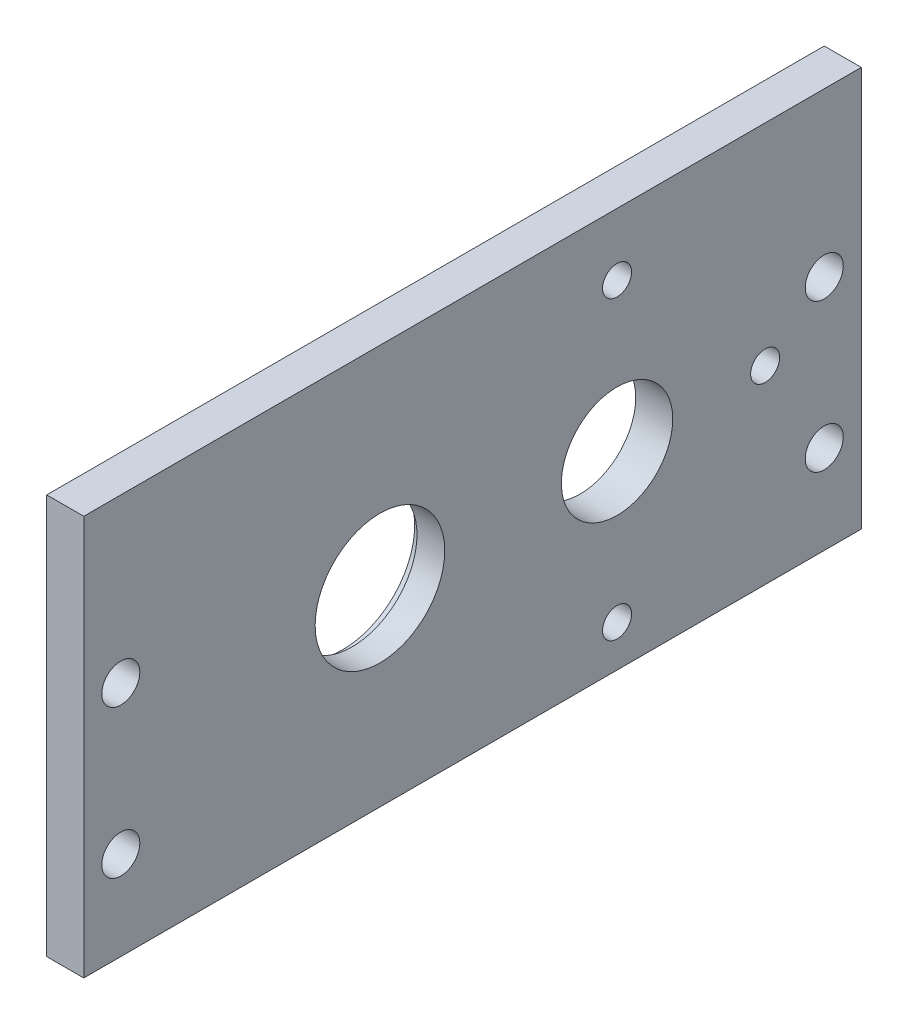
SolidWorks part; units mm, degrees
material "6061-T6 (SS)"
ref_plane "Front Plane" through (0, 0, 0) normal (0, 0, 1) x (1, 0, 0)
ref_plane "Top Plane" through (0, 0, 0) normal (0, 1, 0) x (1, 0, 0)
ref_plane "Right Plane" through (0, 0, 0) normal (1, 0, 0) x (0, 0, -1)
sketch "Sketch1" plane through (0, 0, 0) normal (1, 0, 0) x (0, 0, -1)
  line L0 (76.2, -17.272) -> (76.2, 8.128) construction
  line L1 (-50.8, 36.068) -> (82.55, 36.068)
  line L2 (-50.8, 36.068) -> (-50.8, -32.512)
  line L3 (-50.8, -32.512) -> (82.55, -32.512)
  line L4 (82.55, 36.068) -> (82.55, -32.512)
  line L5 (40.6654, 25.4) -> (15.2654, 0) construction
  line L6 (15.2654, 0) -> (40.6654, -25.4) construction
  line L7 (40.6654, -25.4) -> (66.0654, 0) construction
  line L8 (66.0654, 0) -> (40.6654, 25.4) construction
  line L9 (-44.45, -17.272) -> (-44.45, 8.128) construction
  circle A0 centre (0, 0) radius 33.0327 construction
  circle A1 centre (0, 0) radius 11.1125
  circle A2 centre (40.6654, 0) radius 30 construction
  circle A3 centre (0, 0) radius 12.3063 construction
  circle A5 centre (40.6654, 0) radius 7.6327 construction
  circle A6 centre (40.6654, 0) radius 9.5504
  circle A7 centre (40.6654, 0) radius 25.4 construction
  circle A8 centre (40.6654, 25.4) radius 2.4892
  circle A9 centre (40.6654, -25.4) radius 2.4892
  circle A10 centre (66.0654, 0) radius 2.4892
  circle A11 centre (76.2, -17.272) radius 3.2639
  circle A12 centre (76.2, 8.128) radius 3.2639
  circle A13 centre (-44.45, 8.128) radius 3.2639
  circle A14 centre (-44.45, -17.272) radius 3.2639
  point P30 (0, 0)
  dimension "D1" = 22.225
  dimension "D2" = 60
  dimension "D3" = 24.6126
  dimension "D4" = 19.1008
  dimension "D5" = 15.2654
  dimension "D6" = 66.0654
  dimension "D10" = 4.9784
  dimension "D11" = 50.8
  dimension "D13" = 6.5278
  dimension "D17" = 6.35
  dimension "D7" = 32.512
  dimension "D8" = 133.35
  dimension "D9" = 68.58
  dimension "D12" = 82.55
  dimension "D14" = 15.24
  dimension "D15" = 25.4
  dimension "D16" = 6.35
extrude "Boss-Extrude1" add sketch "Sketch1" along normal blind 6.35
sketch "Sketch2" plane through (0, 0, 0) normal (-1, 0, 0) x (0, 0, 1)
  circle A0 centre (0, 0) radius 12.3063
  dimension "D1" = 24.6126
extrude "Cut-Extrude1" cut sketch "Sketch2" against normal blind 1.5875
